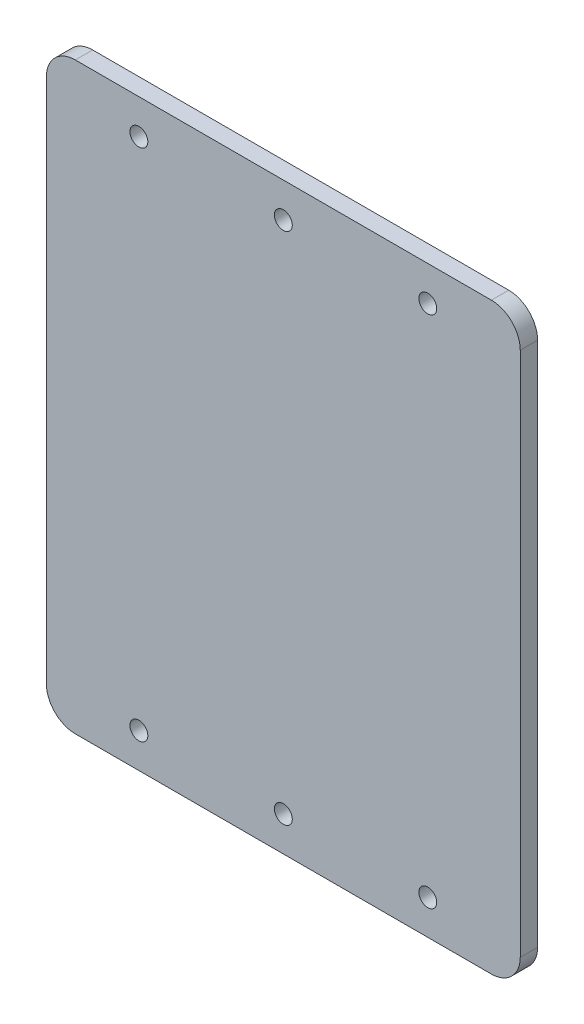
SolidWorks part; units mm, degrees
material "ABS"
ref_plane "前视基准面" through (0, 0, 0) normal (0, 0, 1) x (1, 0, 0)
ref_plane "上视基准面" through (0, 0, 0) normal (0, 1, 0) x (1, 0, 0)
ref_plane "右视基准面" through (0, 0, 0) normal (1, 0, 0) x (0, 0, -1)
other "Configuration Table"
sketch "草图1" plane through (0, 0, 0) normal (0, 0, 1) x (1, 0, 0)
  line L0 (0, 6) -> (82, 6) construction
  line L1 (0, 0) -> (82, 0)
  line L2 (0, 0) -> (0, 101)
  line L3 (0, 101) -> (82, 101)
  line L4 (82, 0) -> (82, 101)
  line L5 (0, 95) -> (82, 95) construction
  circle A0 centre (41, 6) radius 1.55
  circle A1 centre (66, 6) radius 1.55
  circle A2 centre (16, 6) radius 1.55
  circle A3 centre (41, 95) radius 1.55
  circle A4 centre (66, 95) radius 1.55
  circle A5 centre (16, 95) radius 1.55
  dimension "D5" = 3.1
  dimension "D6" = 3.1
  dimension "D7" = 3.1
  dimension "D8" = 3.1
  dimension "D9" = 3.1
  dimension "D10" = 3.1
  dimension "D1" = 82
  dimension "D2" = 101
  dimension "D3" = 6
  dimension "D4" = 6
  dimension "D11" = 25
  dimension "D12" = 25
  dimension "D13" = 25
  dimension "D14" = 25
extrude "凸台-拉伸1" add sketch "草图1" along normal blind 3
fillet "圆角1" radius 5 4 edges at (0, 0, 1.5) (82, 0, 1.5) (82, 101, 1.5) (0, 101, 1.5)
